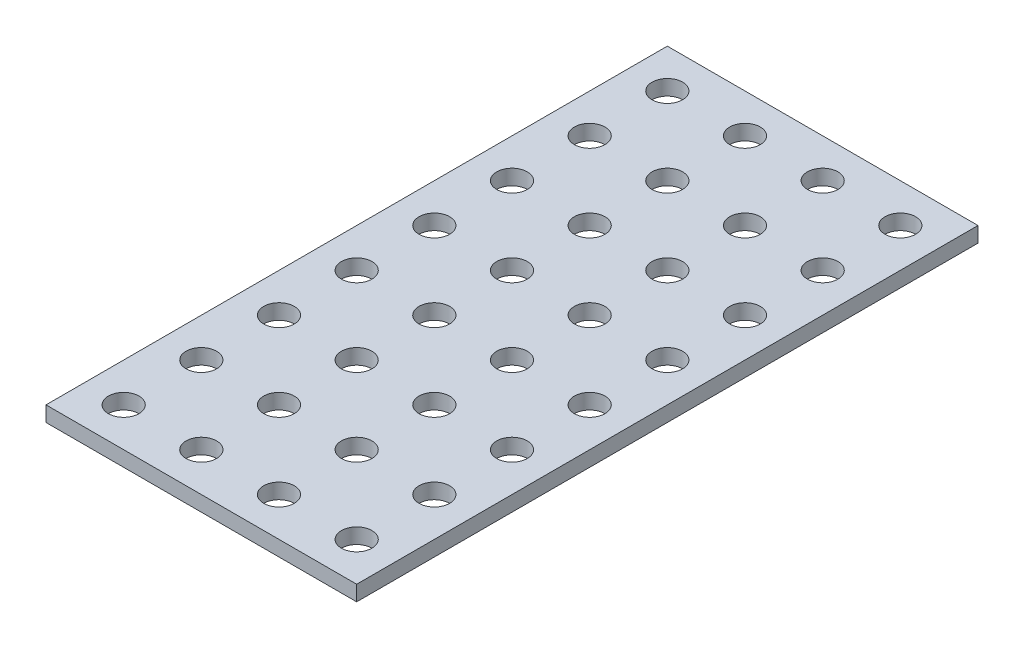
SolidWorks part; units mm, degrees
ref_plane "Front Plane" through (0, 0, 0) normal (0, 0, 1) x (1, 0, 0)
ref_plane "Top Plane" through (0, 0, 0) normal (0, 1, 0) x (1, 0, 0)
ref_plane "Right Plane" through (0, 0, 0) normal (1, 0, 0) x (0, 0, -1)
sketch "Sketch1" plane through (0, 0, 0) normal (0, 1, 0) x (1, 0, 0)
  line L0 (0, 0) -> (2.54, 0) construction
  line L1 (2.54, 0) -> (2.54, 2.54) construction
  line L2 (0, 17.78) -> (0, 19.05) construction
  line L3 (-1.27, 19.05) -> (8.89, 19.05)
  line L4 (-1.27, 19.05) -> (-1.27, -1.27)
  line L5 (-1.27, -1.27) -> (8.89, -1.27)
  line L6 (8.89, 19.05) -> (8.89, -1.27)
  line L8 (-1.27, 17.78) -> (0, 17.78) construction
  line L9 (7.62, -1.27) -> (7.62, 0) construction
  line L10 (7.62, 0) -> (8.89, 0) construction
  circle A32 centre (0, 0) radius 0.5
  circle A33 centre (2.54, 0) radius 0.5
  circle A34 centre (5.08, 0) radius 0.5
  circle A35 centre (7.62, 0) radius 0.5
  circle A36 centre (2.54, 2.54) radius 0.5
  circle A37 centre (5.08, 2.54) radius 0.5
  circle A38 centre (7.62, 2.54) radius 0.5
  circle A39 centre (2.54, 5.08) radius 0.5
  circle A40 centre (5.08, 5.08) radius 0.5
  circle A41 centre (7.62, 5.08) radius 0.5
  circle A42 centre (2.54, 7.62) radius 0.5
  circle A43 centre (5.08, 7.62) radius 0.5
  circle A44 centre (7.62, 7.62) radius 0.5
  circle A45 centre (2.54, 10.16) radius 0.5
  circle A46 centre (5.08, 10.16) radius 0.5
  circle A47 centre (7.62, 10.16) radius 0.5
  circle A48 centre (2.54, 12.7) radius 0.5
  circle A49 centre (5.08, 12.7) radius 0.5
  circle A50 centre (7.62, 12.7) radius 0.5
  circle A51 centre (2.54, 15.24) radius 0.5
  circle A52 centre (5.08, 15.24) radius 0.5
  circle A53 centre (7.62, 15.24) radius 0.5
  circle A54 centre (2.54, 17.78) radius 0.5
  circle A55 centre (5.08, 17.78) radius 0.5
  circle A56 centre (7.62, 17.78) radius 0.5
  circle A57 centre (0, 2.54) radius 0.5
  circle A58 centre (0, 5.08) radius 0.5
  circle A59 centre (0, 7.62) radius 0.5
  circle A60 centre (0, 10.16) radius 0.5
  circle A61 centre (0, 12.7) radius 0.5
  circle A62 centre (0, 15.24) radius 0.5
  circle A63 centre (0, 17.78) radius 0.5
  dimension "D1" = 1
  dimension "D3" = 8
  dimension "D4" = 2.54
  dimension "D5" = 1.27
  dimension "D2" = 4
extrude "Boss-Extrude1" add sketch "Sketch1" along normal blind 0.5
